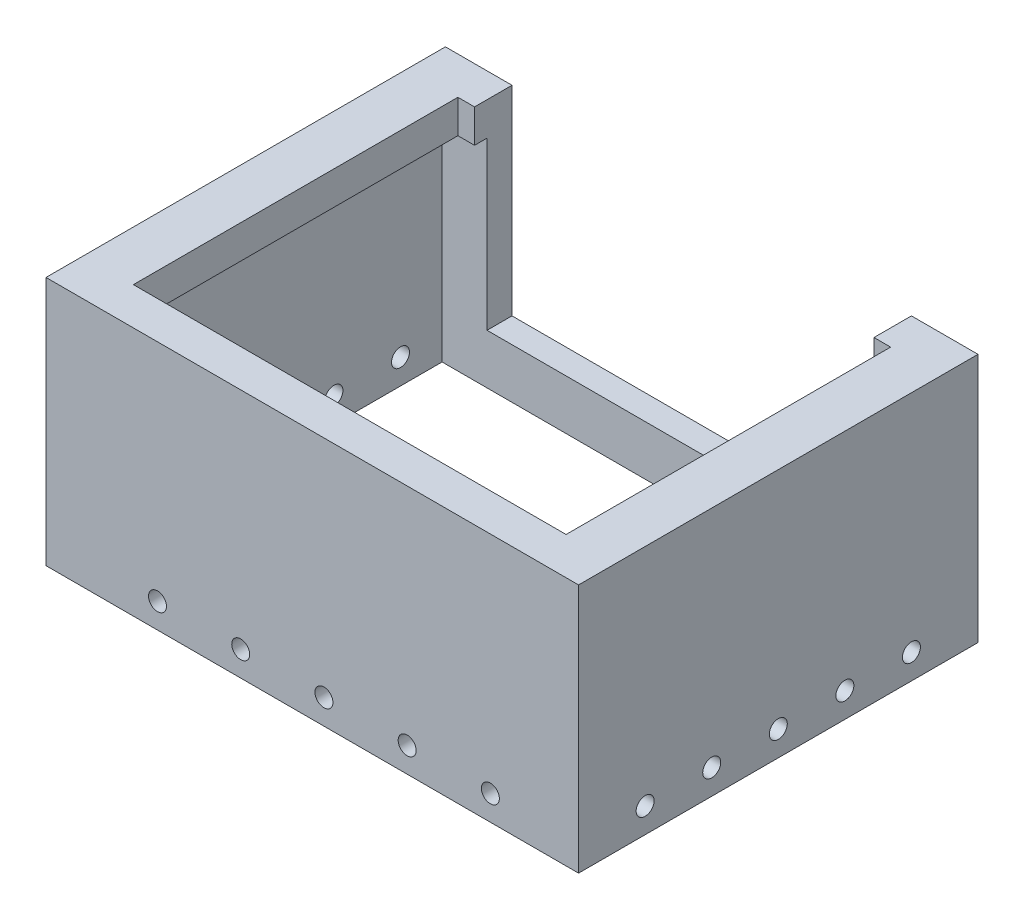
SolidWorks part; units mm, degrees
ref_plane "Front Plane" through (0, 0, 0) normal (0, 0, 1) x (1, 0, 0)
ref_plane "Top Plane" through (0, 0, 0) normal (0, 1, 0) x (1, 0, 0)
ref_plane "Right Plane" through (0, 0, 0) normal (1, 0, 0) x (0, 0, -1)
sketch "Sketch1" plane through (0, 0, 0) normal (0, 1, 0) x (1, 0, 0)
  line L0 (-142.5, 141.1714) -> (-142.5, 152.4214)
  line L2 (-162.5, 152.4214) -> (-162.5, 32.4214)
  line L3 (-162.5, 32.4214) -> (-2.5, 32.4214)
  line L4 (-2.5, 152.4214) -> (-2.5, 32.4214)
  line L5 (-162.5, 152.4214) -> (-2.5, 32.4214) construction
  line L6 (-162.5, 32.4214) -> (-2.5, 152.4214) construction
  line L7 (-17.5, 43.6714) -> (-147.5, 43.6714)
  line L8 (-17.5, 43.6714) -> (-17.5, 141.1714)
  line L10 (-147.5, 43.6714) -> (-147.5, 141.1714)
  line L11 (-17.5, 43.6714) -> (-147.5, 141.1714) construction
  line L12 (-17.5, 141.1714) -> (-147.5, 43.6714) construction
  line L13 (-22.5, 141.1714) -> (-22.5, 152.4214)
  line L14 (-17.5, 141.1714) -> (-22.5, 141.1714)
  line L15 (-147.5, 141.1714) -> (-142.5, 141.1714)
  line L16 (-162.5, 152.4214) -> (-142.5, 152.4214)
  line L17 (-2.5, 152.4214) -> (-22.5, 152.4214)
  point P0 (-82.5, 92.4214)
  point P5 (-82.5, 92.4214)
  dimension "D1" = 160
  dimension "D2" = 120
  dimension "D3" = 130
  dimension "D4" = 20
  dimension "D5" = 20
extrude "Boss-Extrude1" add sketch "Sketch1" along normal blind 10
sketch "Sketch2" plane through (0, 0, 0) normal (0, -1, 0) x (1, 0, 0)
  line L0 (-162.5, -32.4214) -> (-2.5, -152.4214) construction
  line L2 (-156, -144.9214) -> (-156, -39.9214)
  line L3 (-156, -39.9214) -> (-9, -39.9214)
  line L4 (-9, -144.9214) -> (-9, -39.9214)
  line L5 (-156, -144.9214) -> (-9, -39.9214) construction
  line L6 (-156, -39.9214) -> (-9, -144.9214) construction
  line L7 (-142.5, -152.4214) -> (-142.5, -144.9214)
  line L9 (-162.5, -152.4214) -> (-162.5, -32.4214)
  line L10 (-162.5, -32.4214) -> (-2.5, -32.4214)
  line L11 (-2.5, -152.4214) -> (-2.5, -32.4214)
  line L12 (-162.5, -152.4214) -> (-2.5, -32.4214) construction
  line L13 (-162.5, -32.4214) -> (-2.5, -152.4214) construction
  line L14 (-142.5, -141.1714) -> (-142.5, -152.4214) construction
  line L15 (-22.5, -152.4214) -> (-22.5, -144.9214)
  line L16 (-22.5, -152.4214) -> (-22.5, -141.1714) construction
  line L17 (-142.5, -144.9214) -> (-156, -144.9214)
  line L18 (-142.5, -152.4214) -> (-162.5, -152.4214)
  line L19 (-22.5, -144.9214) -> (-9, -144.9214)
  line L20 (-2.5, -152.4214) -> (-22.5, -152.4214)
  point P0 (-82.5, -92.4214)
  point P10 (-82.5, -92.4214)
  dimension "D1" = 147
  dimension "D2" = 105
extrude "Boss-Extrude2" add sketch "Sketch2" along normal blind 65
sketch "Sketch5" plane through (-162.5, 0, 0) normal (-1, 0, 0) x (0, 0, 1)
  line L0 (-152.4214, -57.5) -> (-32.4214, -57.5) construction
  line L1 (-152.4214, 10) -> (-152.4214, -65) construction
  line L2 (-32.4214, 10) -> (-32.4214, -65) construction
  line L3 (-32.4214, -65) -> (-152.4214, -65) construction
  circle A0 centre (-132.4214, -57.5) radius 2.7
  circle A1 centre (-112.4214, -57.5) radius 2.7
  circle A2 centre (-92.4214, -57.5) radius 2.7
  circle A3 centre (-72.4214, -57.5) radius 2.7
  circle A4 centre (-52.4214, -57.5) radius 2.7
  dimension "D2" = 5.4
  dimension "D1" = 7.5
  dimension "D3" = 20
  dimension "D4" = 5
extrude "M5holes" cut sketch "Sketch5" against normal through all
sketch "Sketch6" plane through (0, 0, -39.9214) normal (0, 0, -1) x (-1, 0, 0)
  line L0 (9, -57.5) -> (156, -57.5) construction
  line L1 (9, -65) -> (9, 0) construction
  line L2 (156, -65) -> (156, 0) construction
  line L3 (156, -65) -> (9, -65) construction
  circle A0 centre (29, -57.5) radius 2.7
  circle A1 centre (54, -57.5) radius 2.7
  circle A2 centre (79, -57.5) radius 2.7
  circle A3 centre (104, -57.5) radius 2.7
  circle A4 centre (129, -57.5) radius 2.7
  dimension "D2" = 5.4
  dimension "D1" = 7.5
  dimension "D3" = 20
  dimension "D4" = 5
extrude "M5_holes" cut sketch "Sketch6" against normal blind 25
sketch "Sketch7" plane through (-22.5, 0, 0) normal (-1, 0, 0) x (0, 0, 1)
  line L0 (-152.4214, -65) -> (-144.9214, -65)
  line L1 (-144.9214, -65) -> (-152.4214, -65) construction
  line L2 (-144.9214, -65) -> (-144.9214, -50)
  line L3 (-144.9214, -65) -> (-144.9214, 0) construction
  line L4 (-144.9214, -50) -> (-152.4214, -50)
  line L5 (-152.4214, 10) -> (-152.4214, -65) construction
  line L6 (-152.4214, -50) -> (-152.4214, -65)
  dimension "D1" = 15
extrude "Boss-Extrude3" add sketch "Sketch7" along normal blind 121
